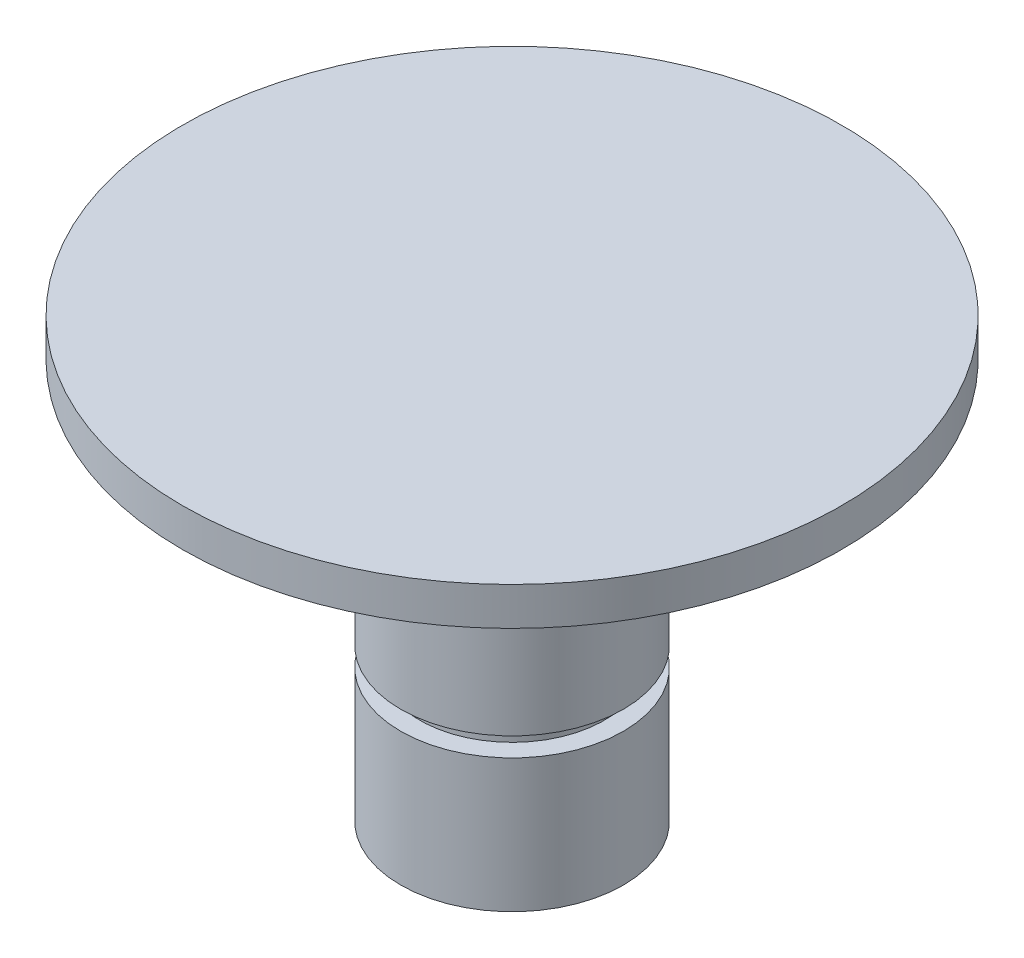
SolidWorks part; units mm, degrees
ref_plane "Front Plane" through (0, 0, 0) normal (0, 0, 1) x (1, 0, 0)
ref_plane "Top Plane" through (0, 0, 0) normal (0, 1, 0) x (1, 0, 0)
ref_plane "Right Plane" through (0, 0, 0) normal (1, 0, 0) x (0, 0, -1)
sketch "Sketch1" plane through (0, 0, 0) normal (0, 1, 0) x (1, 0, 0)
  circle A0 centre (0, 0) radius 5.85
  dimension "D1" = 11.7
extrude "Boss-Extrude1" add sketch "Sketch1" along normal blind 21
sketch "Sketch2" plane through (0, 21, 0) normal (0, 1, 0) x (1, 0, 0)
  circle A0 centre (0, 0) radius 17.3164
extrude "Boss-Extrude2" add sketch "Sketch2" along normal blind 2
ref_plane "Plane1" through (0, 8, 0) normal (0, -1, 0) x (-1, 0, 0)
sketch "Sketch3" plane through (0, 8, 0) normal (0, -1, 0) x (-1, 0, 0)
  circle A0 centre (0, 0) radius 5.85 construction
  circle A1 centre (0, 0) radius 5.85
  circle A2 centre (0, 0) radius 4.85
  dimension "D1" = 1
extrude "Cut-Extrude1" cut sketch "Sketch3" along normal blind 1
sketch "Sketch4" plane through (0, 0, 0) normal (0, -1, 0) x (1, 0, 0)
  circle A0 centre (0, 0) radius 1.5
  dimension "D1" = 3
extrude "Cut-Extrude2" cut sketch "Sketch4" against normal blind 5
sketch "Sketch5" plane through (0, 21, 0) normal (0, -1, 0) x (1, 0, 0)
  circle A0 centre (0, 0) radius 8.85
  circle A1 centre (0, 0) radius 5.85 construction
  circle A2 centre (0, 0) radius 5.85
  dimension "D1" = 3
extrude "Boss-Extrude4" add sketch "Sketch5" along normal blind 3
